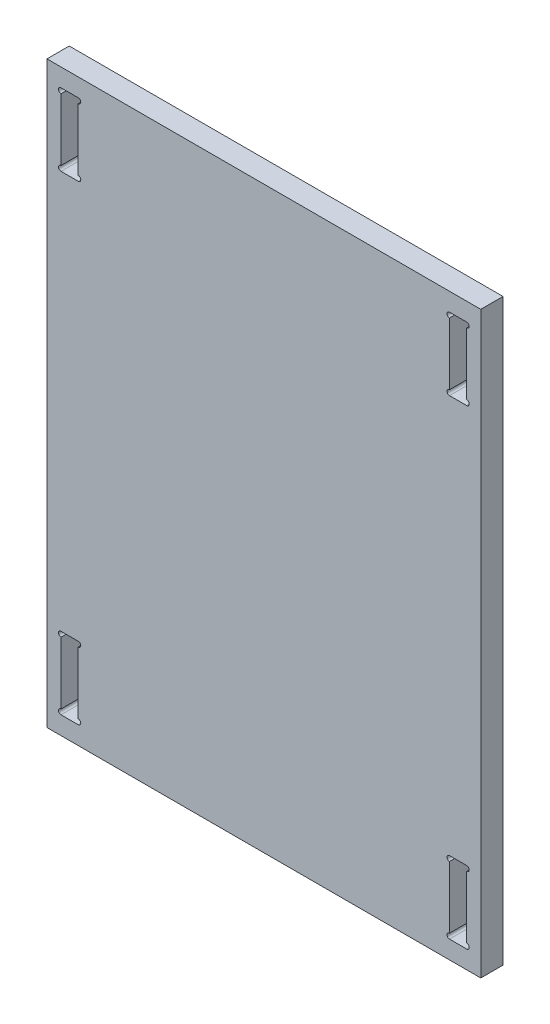
SolidWorks part; units mm, degrees
ref_plane "Front Plane" through (0, 0, 0) normal (0, 0, 1) x (1, 0, 0)
ref_plane "Top Plane" through (0, 0, 0) normal (0, 1, 0) x (1, 0, 0)
ref_plane "Right Plane" through (0, 0, 0) normal (1, 0, 0) x (0, 0, -1)
ref_plane "Plane1" through (0, 0, 1970) normal (0, 0, -1) x (-1, 0, 0)
sketch "Sketch1" plane through (0, 0, 1970) normal (0, 0, -1) x (-1, 0, 0)
  line L0 (-300, 425) -> (-300, -376)
  line L1 (-300, -376) -> (300, -376)
  line L2 (300, -376) -> (300, 425)
  line L3 (300, 425) -> (-300, 425)
  line L12 (256.75, 393) -> (256.75, 307)
  line L13 (280.55, 400) -> (256.75, 400)
  line L14 (280.55, 307) -> (280.55, 393)
  line L15 (256.75, 300) -> (280.55, 300)
  line L16 (-256.75, 300) -> (-280.55, 300)
  line L17 (-280.55, 307) -> (-280.55, 393)
  line L18 (-280.55, 400) -> (-256.75, 400)
  line L19 (-256.75, 393) -> (-256.75, 307)
  line L20 (0, 425) -> (0, -376) construction
  line L21 (-300, 24.5) -> (300, 24.5) construction
  line L22 (-256.75, -344) -> (-256.75, -258)
  line L23 (-280.55, -351) -> (-256.75, -351)
  line L24 (-280.55, -258) -> (-280.55, -344)
  line L25 (-256.75, -251) -> (-280.55, -251)
  line L26 (256.75, -251) -> (280.55, -251)
  line L27 (280.55, -258) -> (280.55, -344)
  line L28 (280.55, -351) -> (256.75, -351)
  line L29 (256.75, -344) -> (256.75, -258)
  arc A8 (256.75, 400) -> (256.75, 393) centre (256.75, 396.5) ccw
  arc A9 (280.55, 393) -> (280.55, 400) centre (280.55, 396.5) ccw
  arc A10 (280.55, 300) -> (280.55, 307) centre (280.55, 303.5) ccw
  arc A11 (256.75, 307) -> (256.75, 300) centre (256.75, 303.5) ccw
  arc A12 (-256.75, 307) -> (-256.75, 300) centre (-256.75, 303.5) cw
  arc A13 (-280.55, 300) -> (-280.55, 307) centre (-280.55, 303.5) cw
  arc A14 (-280.55, 393) -> (-280.55, 400) centre (-280.55, 396.5) cw
  arc A15 (-256.75, 400) -> (-256.75, 393) centre (-256.75, 396.5) cw
  arc A16 (-256.75, -351) -> (-256.75, -344) centre (-256.75, -347.5) ccw
  arc A17 (-280.55, -344) -> (-280.55, -351) centre (-280.55, -347.5) ccw
  arc A18 (-280.55, -251) -> (-280.55, -258) centre (-280.55, -254.5) ccw
  arc A19 (-256.75, -258) -> (-256.75, -251) centre (-256.75, -254.5) ccw
  arc A20 (256.75, -258) -> (256.75, -251) centre (256.75, -254.5) cw
  arc A21 (280.55, -251) -> (280.55, -258) centre (280.55, -254.5) cw
  arc A22 (280.55, -344) -> (280.55, -351) centre (280.55, -347.5) cw
  arc A23 (256.75, -351) -> (256.75, -344) centre (256.75, -347.5) cw
  dimension "D6" = 3.5
  dimension "D7" = 3.5
  dimension "D8" = 3.5
  dimension "D9" = 3.5
  dimension "D1" = 600
  dimension "D2" = 25
  dimension "D3" = 19.45
  dimension "D4" = 23.8
  dimension "D5" = 100
  dimension "D10" = 801
extrude "Boss-Extrude1" add sketch "Sketch1" against normal blind 30.8
